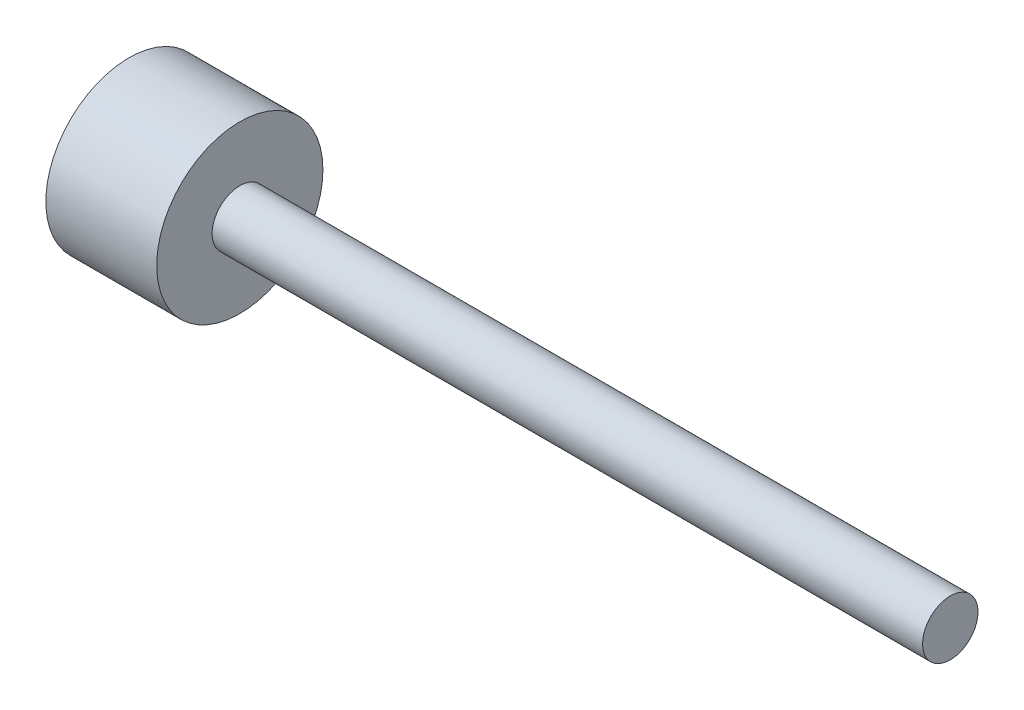
SolidWorks part; units mm, degrees
material "1060 Alloy"
ref_plane "Front Plane" through (0, 0, 0) normal (0, 0, 1) x (1, 0, 0)
ref_plane "Top Plane" through (0, 0, 0) normal (0, 1, 0) x (1, 0, 0)
ref_plane "Right Plane" through (0, 0, 0) normal (1, 0, 0) x (0, 0, -1)
sketch "Sketch1" plane through (0, 0, 0) normal (1, 0, 0) x (0, 0, -1)
  circle A0 centre (0, 0) radius 9.525
  dimension "D1" = 19.05
extrude "Boss-Extrude1" add sketch "Sketch1" along normal blind 12.7
sketch "Sketch2" plane through (12.7, 0, 0) normal (1, 0, 0) x (0, 0, -1)
  circle A0 centre (0, 0) radius 3.175
  dimension "D1" = 6.35
extrude "Boss-Extrude2" add sketch "Sketch2" along normal blind 94.11 from surface at -12.7 starting at face at (0, 0, -9.525)
